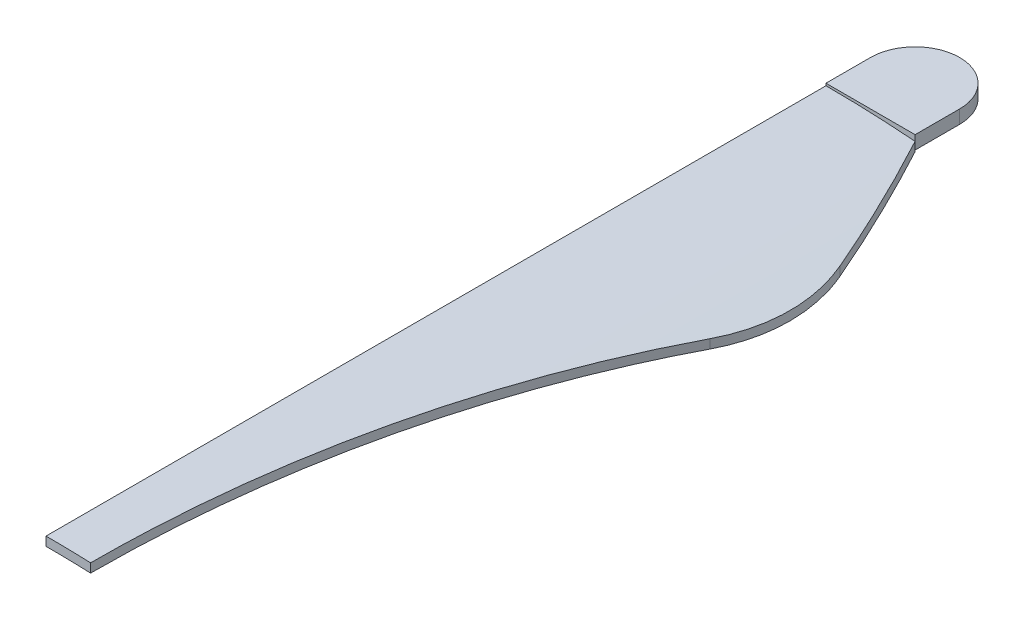
SolidWorks part; units mm, degrees
ref_plane "前视基准面" through (0, 0, 0) normal (0, 0, 1) x (1, 0, 0)
ref_plane "上视基准面" through (0, 0, 0) normal (0, 1, 0) x (1, 0, 0)
ref_plane "右视基准面" through (0, 0, 0) normal (1, 0, 0) x (0, 0, -1)
sketch "草图2" plane through (0, 0, 0) normal (0, 0, 1) x (1, 0, 0)
  line L0 (0, 0) -> (0, 511.8123) construction
  line L1 (80, -10.4941) -> (80, -6.4415)
  line L2 (0, 0) -> (-90.2296, 0) construction
  line L3 (0, -4) -> (0, 0)
  arc A0 (0, 0) -> (80, -6.4415) centre (0, -500) cw
  arc A1 (0, -4) -> (80, -10.4941) centre (0, -500) cw
  arc A2 (0, 0) -> (96.3816, -9.3773) centre (0, -500) cw construction
  arc A3 (0, -4) -> (95.6106, -13.3023) centre (0, -500) cw construction
  dimension "D1" = 500
  dimension "D2" = 80
  dimension "D3" = 4
extrude "凸台-拉伸1" add sketch "草图2" along normal blind 350
sketch "草图3" plane through (0, 0, 0) normal (0, 1, 0) x (1, 0, 0)
  line L0 (0, 0) -> (0, 20)
  line L1 (40, 20) -> (40, 0)
  line L4 (40, 0) -> (0, 0)
  arc A0 (40, 20) -> (0, 20) centre (20, 20) ccw
  dimension "D1" = 40
  dimension "D2" = 20
extrude "凸台-拉伸2" add sketch "草图3" along normal blind 1 and the other way blind 5
sketch "草图4" plane through (0, 1, 0) normal (0, 1, 0) x (1, 0, 0)
  line L0 (0, -350) -> (20, -350)
  line L1 (0, -350) -> (80, -350) construction
  line L3 (40, 0) -> (40, 103.7028)
  line L4 (40, 103.7028) -> (-64.5318, 103.7028)
  line L5 (-64.5318, 103.7028) -> (-64.5318, -350)
  line L6 (-64.5318, -350) -> (0, -350)
  arc A0 (40, 0) -> (68.4954, -62.261) centre (-563.2858, -313.7615) cw
  arc A1 (68.4954, -62.261) -> (67.6518, -119.771) centre (-1.1863, -90) cw
  arc A2 (20, -350) -> (67.6518, -119.771) centre (600, -350) cw
  point P12 (-64.5318, 103.7028)
  dimension "D1" = 20
  dimension "D2" = 680
  dimension "D4" = 75
  dimension "D5" = 580
  dimension "D3" = 260
  dimension "D6" = 104.5318
  dimension "D7" = 103.7028
extrude "切除-拉伸1" cut sketch "草图4" against normal through all both and the other way through all flip side to cut
